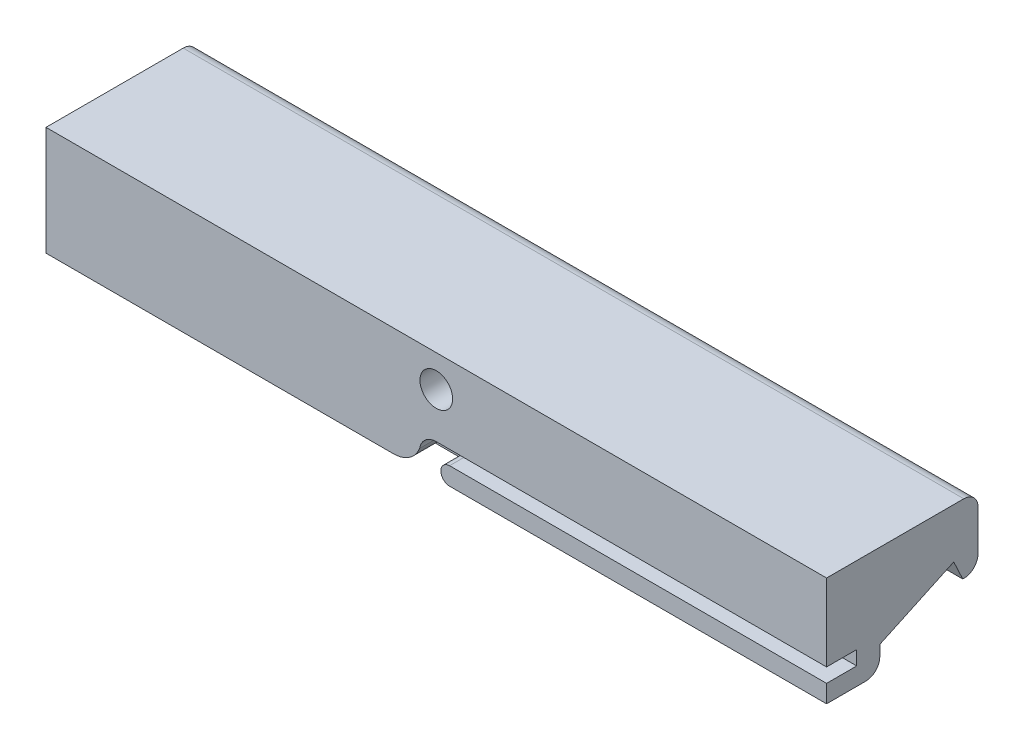
SolidWorks part; units mm, degrees
other "Markup1"
sketch "Sketch5" plane through (110, 0, 0) normal (0.0863, -0.8703, 0.4849) x (0.7955, -0.2329, -0.5594)
ref_plane "Front Plane" through (0, 0, 0) normal (0, 0, 1) x (1, 0, 0)
ref_plane "Top Plane" through (0, 0, 0) normal (0, 1, 0) x (1, 0, 0)
ref_plane "Right Plane" through (0, 0, 0) normal (1, 0, 0) x (0, 0, -1)
sketch "Sketch1" plane through (0, 0, 0) normal (1, 0, 0) x (0, 0, -1)
  line L0 (0, 0) -> (5.4995, 0)
  line L2 (21.3407, 7.6355) -> (21.3407, 13.3601)
  line L3 (19.3407, 15.3601) -> (0, 15.3601)
  line L4 (0, 15.3601) -> (0, 0)
  line L6 (19.1904, 5.6412) -> (17.9225, 8.3601)
  line L7 (17.9225, 8.3601) -> (7.5, 3.5)
  line L8 (7.5, 3.5) -> (7.5, 2.0005)
  arc A0 (19.3407, 15.3601) -> (21.3407, 13.3601) centre (19.3407, 13.3601) cw
  arc A1 (19.1904, 5.6412) -> (21.3407, 7.6355) centre (19.3407, 7.6355) ccw
  arc A2 (5.4995, 0) -> (7.5, 2.0005) centre (5.4995, 2.0005) ccw
  dimension "D7" = 4
  dimension "D4" = 4
  dimension "D8" = 4.0011
  dimension "D3" = 11.5
  dimension "D1" = 7.5
  dimension "D5" = 7
  dimension "D6" = 3
extrude "ProfileBoss-Extrude1" add sketch "Sketch1" along normal blind 110
sketch "Sketch3" plane through (0, 0, 0) normal (0, 0, 1) x (1, 0, 0)
  line L0 (0, 15.3601) -> (0, 0) construction
  circle A0 centre (55, 10.8601) radius 2.3
  dimension "D1" = 4.6
  dimension "D4" = 4.5
  dimension "D2" = 55
extrude "MountingHolesCut-Extrude3" cut sketch "Sketch3" against normal blind 4.5
sketch "Sketch4" plane through (0, 0, 0) normal (0, 0, 1) x (1, 0, 0)
  line L0 (110, 15.3601) -> (110, 0) construction
  line L1 (55, 4.5) -> (110, 4.5)
  line L4 (110, 4.5) -> (110, 2.5)
  line L5 (48.9895, 0) -> (56.8729, 0)
  line L6 (110, 0) -> (0, 0) construction
  line L9 (56.8729, 2.5) -> (110, 2.5)
  line L10 (0, 15.3601) -> (0, 0) construction
  arc A1 (56.8729, 2.5) -> (56.8729, 0) centre (56.8928, 1.25) ccw
  arc A2 (52.6533, 2.5) -> (55, 4.5) centre (55, 2.1233) cw
  arc A3 (48.9895, 0) -> (52.6533, 2.5) centre (48.9895, 3.9347) ccw
  dimension "D7" = 1.2502
  dimension "D1" = 2
  dimension "D2" = 2.5
  dimension "D6" = 55
  dimension "D3" = 3.6638
  dimension "D4" = 2.3467
  dimension "D5" = 1.8729
extrude "XAxisCableCut-Extrude1" cut sketch "Sketch4" against normal blind 4.25
equation "\"LightStripShortLength\"= 80mm"
equation "\"D1@ProfileBoss-Extrude1\" = \"LightStripMidLength\""
equation "\"LightStripWidth\"= 11.5mm'Spec"
equation "\"D3@Sketch1\"=\"LightStripWidth\""
equation "\"LightStripGuideMountingHoleFromMiddle\"= \"LightStripMidLength\" / 2"
equation "\"D2@Sketch3\"=\"LightStripGuideMountingHoleFromMiddle\""
equation "\"LedStripLength\"= 270mm'Spec"
equation "\"LightStripMidLength\"= \"LedStripLength\" - \"LightStripShortLength\" * 2"
equation "\"LightStripGuideMountingHoleFromTop\"= 4.5mm"
equation "\"D4@Sketch3\"=\"LightStripGuideMountingHoleFromTop\""
equation "\"D6@Sketch4\"=\"LightStripMidLength\"/2"
